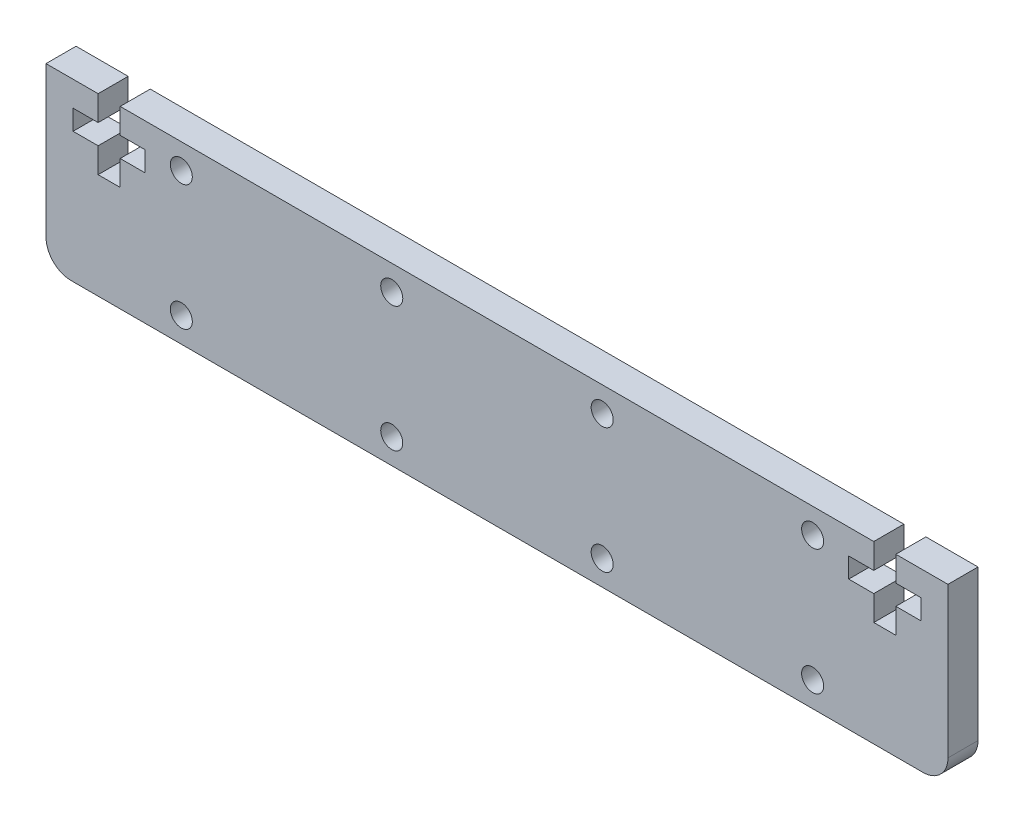
SolidWorks part; units mm, degrees
ref_plane "Front Plane" through (0, 0, 0) normal (0, 0, 1) x (1, 0, 0)
ref_plane "Top Plane" through (0, 0, 0) normal (0, 1, 0) x (1, 0, 0)
ref_plane "Right Plane" through (0, 0, 0) normal (1, 0, 0) x (0, 0, -1)
sketch "Sketch1" plane through (0, 0, 0) normal (0, 0, 1) x (1, 0, 0)
  line L0 (-45, 0) -> (45, 0) construction
  line L1 (-45, -8.75) -> (45, -8.75)
  line L2 (-45, -8.75) -> (-45, 8.75)
  line L3 (-45, 8.75) -> (45, 8.75) construction
  line L4 (45, -8.75) -> (45, 8.75)
  line L5 (-45, -8.75) -> (45, 8.75) construction
  line L6 (-45, 8.75) -> (45, -8.75) construction
  line L19 (0, 8.75) -> (0, -8.75) construction
  line L47 (-37.6, 8.75) -> (-37.6, 6.25)
  line L48 (-37.6, 6.25) -> (-35.1, 6.25)
  line L49 (-35.1, 6.25) -> (-35.1, 4.25)
  line L50 (-35.1, 4.25) -> (-37.6, 4.25)
  line L51 (-37.6, 4.25) -> (-37.6, 1.75)
  line L52 (-37.6, 1.75) -> (-39.8, 1.75)
  line L70 (-39.8, 1.75) -> (-39.8, 4.25)
  line L71 (-39.8, 4.25) -> (-42.3, 4.25)
  line L72 (-42.3, 4.25) -> (-42.3, 6.25)
  line L73 (-42.3, 6.25) -> (-39.8, 6.25)
  line L74 (-39.8, 6.25) -> (-39.8, 8.75)
  line L75 (39.8, 6.25) -> (39.8, 8.75)
  line L76 (42.3, 6.25) -> (39.8, 6.25)
  line L77 (42.3, 4.25) -> (42.3, 6.25)
  line L78 (39.8, 4.25) -> (42.3, 4.25)
  line L79 (39.8, 1.75) -> (39.8, 4.25)
  line L80 (37.6, 1.75) -> (39.8, 1.75)
  line L81 (37.6, 4.25) -> (37.6, 1.75)
  line L82 (35.1, 4.25) -> (37.6, 4.25)
  line L83 (35.1, 6.25) -> (35.1, 4.25)
  line L84 (37.6, 6.25) -> (35.1, 6.25)
  line L85 (37.6, 8.75) -> (37.6, 6.25)
  line L86 (-45, 8.75) -> (-39.8, 8.75)
  line L87 (-37.6, 8.75) -> (37.6, 8.75)
  line L88 (39.8, 8.75) -> (45, 8.75)
  circle A5 centre (-10.5, 6.25) radius 1.1
  circle A9 centre (-10.5, -6.25) radius 1.1
  circle A12 centre (10.5, -6.25) radius 1.1
  circle A13 centre (10.5, 6.25) radius 1.1
  circle A14 centre (-31.5, 6.25) radius 1.1
  circle A16 centre (-31.5, -6.25) radius 1.1
  circle A17 centre (31.5, -6.25) radius 1.1
  circle A18 centre (31.5, 6.25) radius 1.1
  point P0 (0, 0)
  dimension "D3" = 2.2
  dimension "D12" = 2.2
  dimension "D1" = 90
  dimension "D2" = 17.5
  dimension "D5" = 10.5
  dimension "D6" = 6.25
  dimension "D11" = 21
  dimension "D13" = 2.2
  dimension "D14" = 2.5
  dimension "D15" = 2
  dimension "D16" = 2.5
  dimension "D17" = 35.1
  dimension "D18" = 1.75
extrude "Boss-Extrude1" add sketch "Sketch1" along normal blind 3
fillet "Fillet1" radius 2.5 2 edges at (-45, -8.75, 1.5) (45, -8.75, 1.5)
